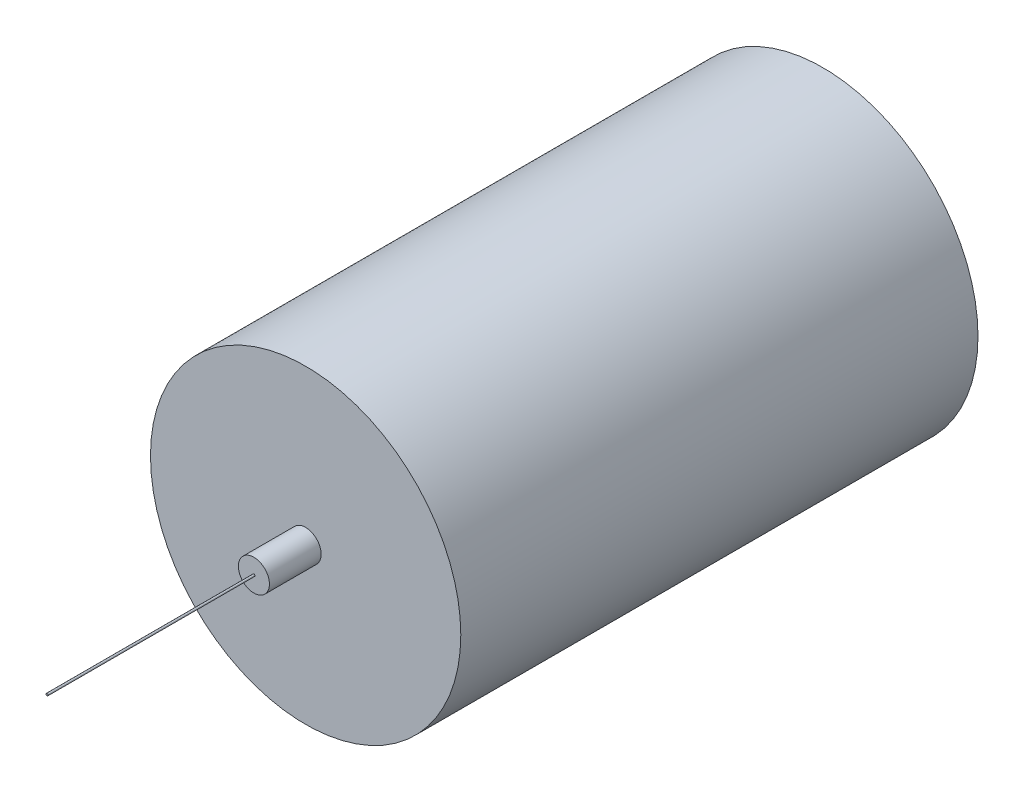
SolidWorks part; units mm, degrees
ref_plane "Front Plane" through (0, 0, 0) normal (0, 0, 1) x (1, 0, 0)
ref_plane "Top Plane" through (0, 0, 0) normal (0, 1, 0) x (1, 0, 0)
ref_plane "Right Plane" through (0, 0, 0) normal (1, 0, 0) x (0, 0, -1)
sketch "Sketch1" plane through (0, 0, 0) normal (0, 0, 1) x (1, 0, 0)
  circle A0 centre (0, 0) radius 1.5
  circle A1 centre (0, 0) radius 0.5
extrude "Boss-Extrude1" add sketch "Sketch1" along normal blind 4
sketch "Sketch2" plane through (0, 0, 4) normal (0, 0, 1) x (1, 0, 0)
  circle A0 centre (0, 0) radius 1.5
  circle A1 centre (0, 0) radius 0.15
extrude "Boss-Extrude2" add sketch "Sketch2" along normal blind 1
sketch "Sketch3" plane through (0, 0, 5) normal (0, 0, 1) x (1, 0, 0)
  circle A0 centre (0, 0) radius 0.15
extrude "Boss-Extrude3" add sketch "Sketch3" along normal blind 0.5 separate body
sketch "Sketch4" plane through (0, 0, 5.5) normal (0, 0, 1) x (1, 0, 0)
  circle A0 centre (0, 0) radius 0.01
extrude "Boss-Extrude5" add sketch "Sketch4" along normal blind 2
